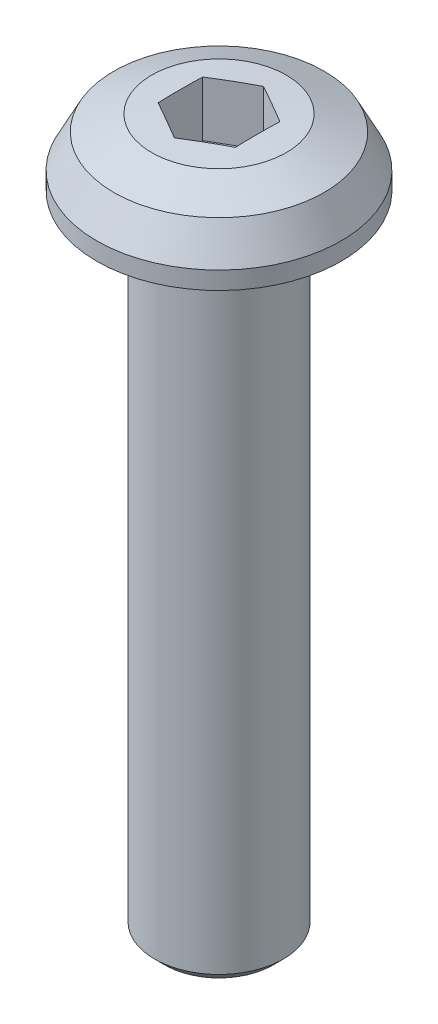
SolidWorks part; units mm, degrees
ref_plane "Front Plane" through (0, 0, 0) normal (0, 0, 1) x (1, 0, 0)
ref_plane "Top Plane" through (0, 0, 0) normal (0, 1, 0) x (1, 0, 0)
ref_plane "Right Plane" through (0, 0, 0) normal (1, 0, 0) x (0, 0, -1)
sketch "Sketch1" plane through (0, 0, 0) normal (0, 0, 1) x (1, 0, 0)
  line L0 (0, -25) -> (2.1, -25)
  line L1 (2.1, -25) -> (2.5, -24.6)
  line L2 (2.5, -24.6) -> (2.5, 0)
  line L3 (2.5, 0) -> (4.75, 0)
  line L4 (4.75, 0) -> (4.75, 0.6875)
  line L5 (4.75, 0.6875) -> (4.085, 1.98)
  line L6 (4.085, 1.98) -> (2.6125, 2.585)
  line L7 (2.6125, 2.585) -> (0, 2.75)
  line L8 (0, 2.75) -> (0, -25)
  line L9 (0, -10) -> (0, 1000) construction
revolve "Revolve1" add sketch "Sketch1" angle 360 about L9
cosmetic thread "Cosmetic Thread1" parameters "D1"=24.6, "D2"=4.134
ref_plane "Plane1" through (0, 2.75, 0) normal (0, 1, 0) x (1, 0, 0)
sketch "Sketch2" plane through (0, 2.75, 0) normal (0, 1, 0) x (1, 0, 0)
  line L0 (1.5, -0.866) -> (0, -1.7321)
  line L1 (0, -1.7321) -> (-1.5, -0.866)
  line L2 (-1.5, -0.866) -> (-1.5, 0.866)
  line L3 (-1.5, 0.866) -> (0, 1.7321)
  line L4 (0, 1.7321) -> (1.5, 0.866)
  line L5 (1.5, 0.866) -> (1.5, -0.866)
extrude "Cut-Extrude1" cut sketch "Sketch2" against normal blind 2.25
